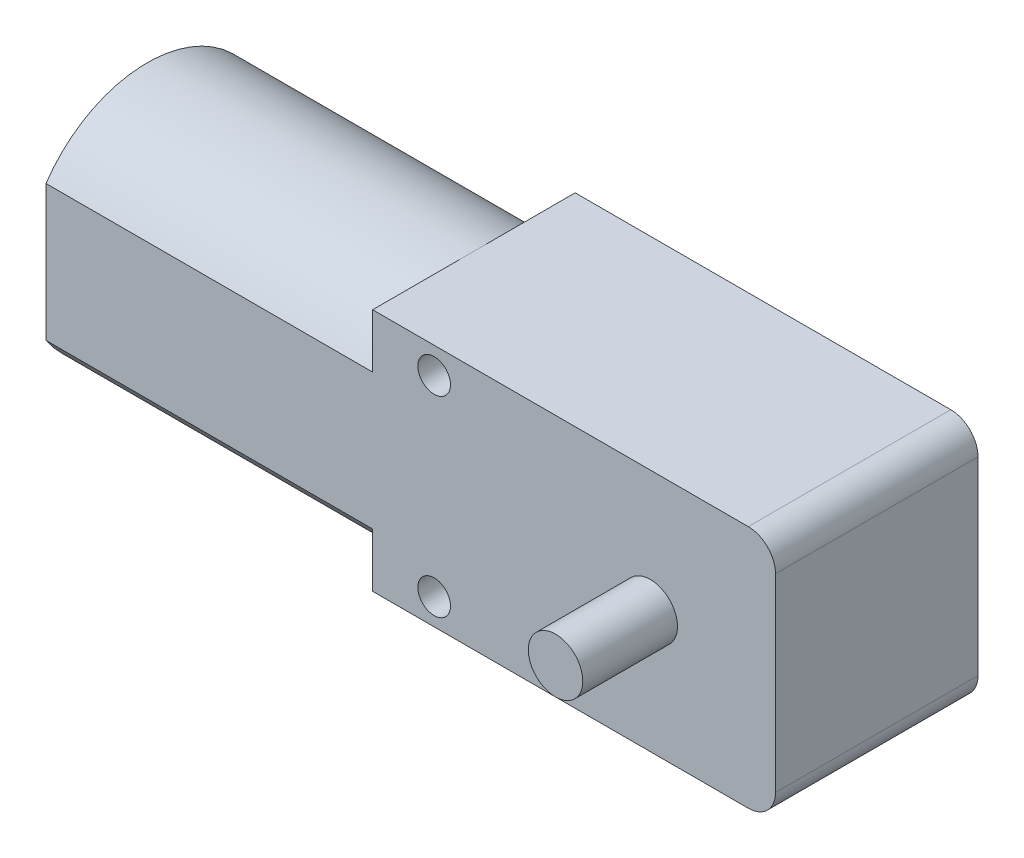
SolidWorks part; units mm, degrees
ref_plane "Front Plane" through (0, 0, 0) normal (0, 0, 1) x (1, 0, 0)
ref_plane "Top Plane" through (0, 0, 0) normal (0, 1, 0) x (1, 0, 0)
ref_plane "Right Plane" through (0, 0, 0) normal (1, 0, 0) x (0, 0, -1)
sketch "Sketch1" plane through (0, 0, 0) normal (0, 0, 1) x (1, 0, 0)
  line L1 (0, 0) -> (37, 0)
  line L2 (0, 0) -> (0, 22.4)
  line L3 (0, 22.4) -> (37, 22.4)
  line L4 (37, 0) -> (37, 22.4)
  dimension "D1" = 37
  dimension "D2" = 22.4
extrude "Boss-Extrude1" add sketch "Sketch1" along normal blind 18.6
sketch "Sketch2" plane through (0, 0, 0) normal (-1, 0, 0) x (0, 0, 1)
  line L0 (18.6, 22.4) -> (18.6, 0) construction
  line L1 (18.6, 22.4) -> (0, 22.4) construction
  line L2 (0, 17.441) -> (0, 4.959)
  line L4 (18.6, 17.441) -> (18.6, 4.959)
  arc A0 (0, 4.959) -> (18.6, 4.959) centre (9.3, 11.2) ccw
  arc A1 (18.6, 17.441) -> (0, 17.441) centre (9.3, 11.2) ccw
  dimension "D1" = 9.3
  dimension "D2" = 11.2
extrude "Boss-Extrude2" add sketch "Sketch2" along normal blind 30
sketch "Sketch3" plane through (0, 0, 18.6) normal (0, 0, 1) x (1, 0, 0)
  line L0 (37, 0) -> (37, 22.4) construction
  line L1 (37, 22.4) -> (0, 22.4) construction
  circle A0 centre (25.5, 11.2) radius 2.5
  dimension "D1" = 11.5
  dimension "D2" = 11.2
extrude "Boss-Extrude3" add sketch "Sketch3" along normal blind 8.7 and the other way offset from surface (27.3 mm away) 8.7 other way up to face at (1.75, 11.2, 0)
sketch "Sketch4" plane through (0, 0, 18.6) normal (0, 0, 1) x (1, 0, 0)
  line L0 (37, 22.4) -> (0, 22.4) construction
  circle A0 centre (5.65, 20) radius 1.5
  circle A1 centre (5.65, 2.4) radius 1.5
  circle A2 centre (25.5, 11.2) radius 2.5 construction
  dimension "D3" = 3
  dimension "D4" = 3
  dimension "D5" = 0
  dimension "D6" = 2.4
  dimension "D1" = 19.85
  dimension "D2" = 17.6
extrude "Cut-Extrude1" cut sketch "Sketch4" against normal up to surface (18.6 mm away) up to face at (23, 11.2, 0)
fillet "Fillet2" radius 2.5 2 edges at (37, 0, 9.3) (37, 22.4, 9.3)
